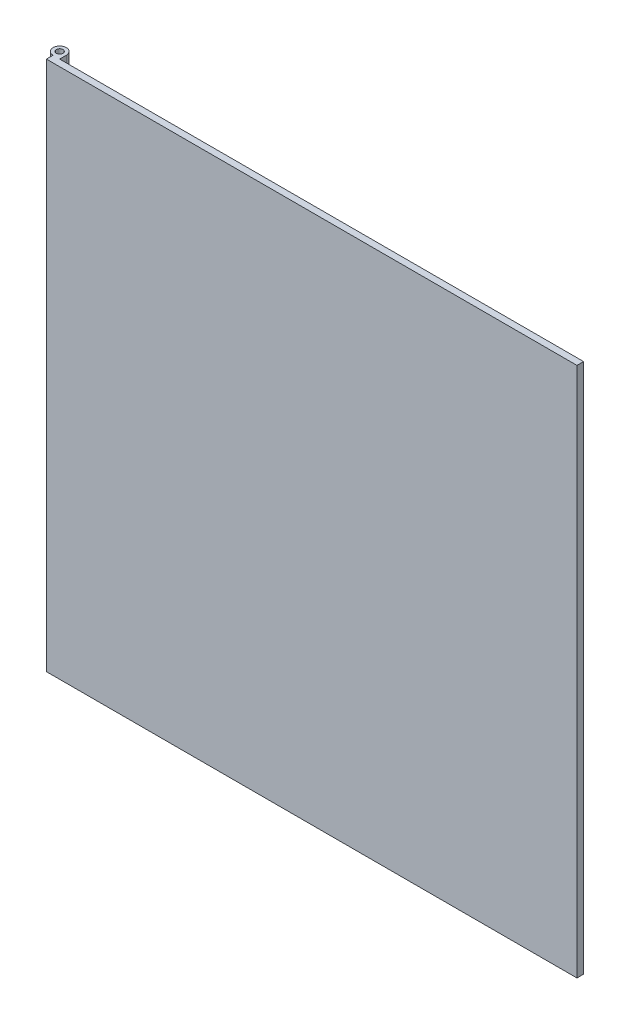
SolidWorks part; units mm, degrees
ref_plane "Plan de face" through (0, 0, 0) normal (0, 0, 1) x (1, 0, 0)
ref_plane "Plan de dessus" through (0, 0, 0) normal (0, 1, 0) x (1, 0, 0)
ref_plane "Plan de droite" through (0, 0, 0) normal (1, 0, 0) x (0, 0, -1)
sketch "Esquisse1" plane through (0, 0, 0) normal (0, 0, 1) x (1, 0, 0)
  line L1 (0, 0) -> (80, 0)
  line L2 (0, 0) -> (0, 80)
  line L3 (0, 80) -> (80, 80)
  line L4 (80, 0) -> (80, 80)
  dimension "D1" = 80
  dimension "D2" = 80
extrude "Boss.-Extru.1" add sketch "Esquisse1" along normal blind 1
sketch "Esquisse2" plane through (0, 80, 0) normal (0, 1, 0) x (1, 0, 0)
  line L0 (1, 0) -> (1, 1)
  line L1 (80, 0) -> (0, 0) construction
  line L2 (0, 1) -> (0, 0) construction
  line L3 (1, 0) -> (0, 0)
  arc A0 (0, 0) -> (1, 1) centre (0, 1) cw
  circle A1 centre (0, 1) radius 0.5
  dimension "D1" = 1
  dimension "D2" = 1
  dimension "D3" = 1
extrude "Boss.-Extru.2" add sketch "Esquisse2" against normal up to surface (80 mm away) up to face at (40, 0, 0.5)
